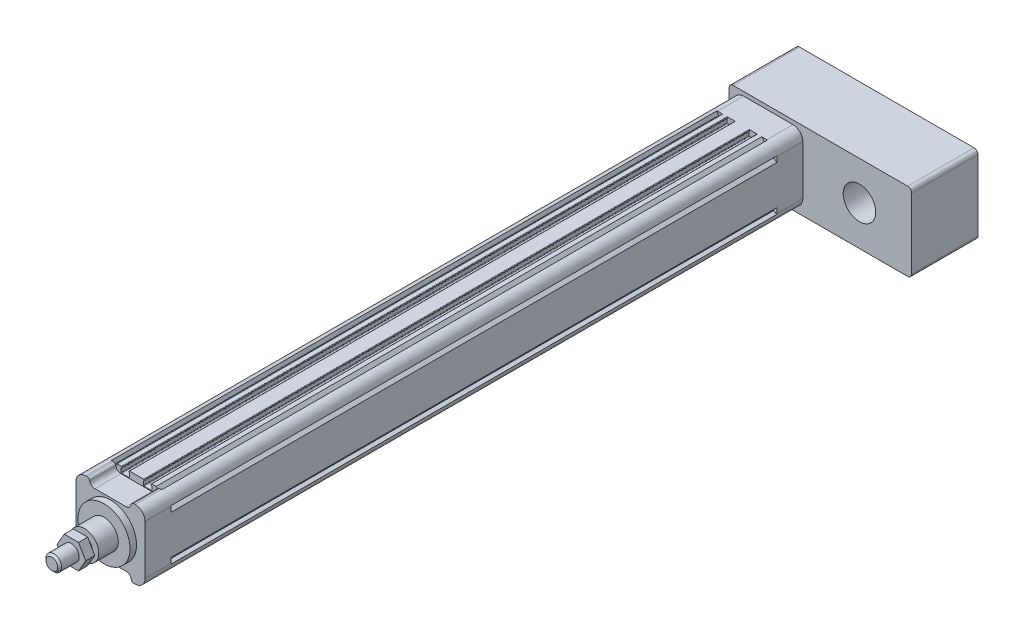
SolidWorks part; units mm, degrees
ref_plane "Front" through (0, 0, 0) normal (0, 0, 1) x (1, 0, 0)
ref_plane "Top" through (0, 0, 0) normal (0, 1, 0) x (1, 0, 0)
ref_plane "Right" through (0, 0, 0) normal (1, 0, 0) x (0, 0, -1)
sketch "草图1" plane through (0, 0, 0) normal (0, 0, 1) x (1, 0, 0)
  line L0 (19.7737, 3) -> (23.3, 3)
  line L1 (23.3, 3) -> (23.3, -3)
  line L2 (23.3, -3) -> (19.7737, -3)
  line L3 (-19.7737, -3) -> (-23.3, -3)
  line L4 (-23.3, -3) -> (-23.3, 3)
  line L5 (-23.3, 3) -> (-19.7737, 3)
  line L6 (-18.2, 24) -> (-19.4434, 26.4869)
  line L7 (-26.4869, 19.4434) -> (-24, 18.2)
  line L8 (-24, 18.2) -> (-24, 17.1)
  line L9 (-24, 17.1) -> (-26.5, 15)
  line L10 (-26.5, 15) -> (-26.5, -15)
  line L11 (-26.5, -15) -> (-24, -17.1)
  line L12 (-24, -17.1) -> (-24, -18.2)
  line L13 (-24, -18.2) -> (-26.4869, -19.4434)
  line L14 (-19.4434, -26.4869) -> (-18.2, -24)
  line L15 (-18.2, -24) -> (-17.1, -24)
  line L16 (-17.1, -24) -> (-15, -26.5)
  line L17 (-15, -26.5) -> (-11.65, -26.5)
  line L18 (-11.25, -26.1) -> (-11.25, -25.6)
  line L19 (-11.65, -25.2) -> (-11.75, -25.2)
  line L20 (-11.75, -25.2) -> (-11.75, -22.4)
  line L21 (-11.35, -22) -> (-5.65, -22)
  line L22 (-5.25, -22.4) -> (-5.25, -25.2)
  line L23 (-5.25, -25.2) -> (-5.35, -25.2)
  line L24 (-5.75, -25.6) -> (-5.75, -26.1)
  line L25 (-5.35, -26.5) -> (5.35, -26.5)
  line L26 (5.75, -26.1) -> (5.75, -25.6)
  line L27 (5.35, -25.2) -> (5.25, -25.2)
  line L28 (5.25, -25.2) -> (5.25, -22.4)
  line L29 (5.65, -22) -> (11.35, -22)
  line L30 (11.75, -22.4) -> (11.75, -25.2)
  line L31 (11.75, -25.2) -> (11.65, -25.2)
  line L32 (11.25, -25.6) -> (11.25, -26.1)
  line L33 (11.65, -26.5) -> (15, -26.5)
  line L34 (15, -26.5) -> (17.1, -24)
  line L35 (17.1, -24) -> (18.2, -24)
  line L36 (18.2, -24) -> (19.4434, -26.4869)
  line L37 (26.4869, -19.4434) -> (24, -18.2)
  line L38 (24, -18.2) -> (24, -17.1)
  line L39 (24, -17.1) -> (26.5, -15)
  line L40 (26.5, -15) -> (26.5, 15)
  line L41 (26.5, 15) -> (24, 17.1)
  line L42 (24, 17.1) -> (24, 18.2)
  line L43 (24, 18.2) -> (26.4869, 19.4434)
  line L44 (19.4434, 26.4869) -> (18.2, 24)
  line L45 (18.2, 24) -> (17.1, 24)
  line L46 (17.1, 24) -> (15, 26.5)
  line L47 (15, 26.5) -> (11.65, 26.5)
  line L48 (11.25, 26.1) -> (11.25, 25.6)
  line L49 (11.65, 25.2) -> (11.75, 25.2)
  line L50 (11.75, 25.2) -> (11.75, 22.4)
  line L51 (11.35, 22) -> (5.65, 22)
  line L52 (5.25, 22.4) -> (5.25, 25.2)
  line L53 (5.25, 25.2) -> (5.35, 25.2)
  line L54 (5.75, 25.6) -> (5.75, 26.1)
  line L55 (5.35, 26.5) -> (-5.35, 26.5)
  line L56 (-5.75, 26.1) -> (-5.75, 25.6)
  line L57 (-5.35, 25.2) -> (-5.25, 25.2)
  line L58 (-5.25, 25.2) -> (-5.25, 22.4)
  line L59 (-5.65, 22) -> (-11.35, 22)
  line L60 (-11.75, 22.4) -> (-11.75, 25.2)
  line L61 (-11.75, 25.2) -> (-11.65, 25.2)
  line L62 (-11.25, 25.6) -> (-11.25, 26.1)
  line L63 (-11.65, 26.5) -> (-15, 26.5)
  line L64 (-15, 26.5) -> (-17.1, 24)
  line L65 (-17.1, 24) -> (-18.2, 24)
  arc A0 (19.7737, 3) -> (-19.7737, 3) centre (0, 0) ccw
  arc A1 (-19.7737, -3) -> (19.7737, -3) centre (0, 0) ccw
  circle A2 centre (19, 19) radius 2.1
  circle A3 centre (19, -19) radius 2.1
  circle A4 centre (-19, -19) radius 2.1
  circle A5 centre (-19, 19) radius 2.1
  arc A6 (-19.4434, 26.4869) -> (-26.4869, 19.4434) centre (-19, 19) ccw
  arc A7 (-26.4869, -19.4434) -> (-19.4434, -26.4869) centre (-19, -19) ccw
  arc A8 (-11.65, -26.5) -> (-11.25, -26.1) centre (-11.65, -26.1) ccw
  arc A9 (-11.25, -25.6) -> (-11.65, -25.2) centre (-11.65, -25.6) ccw
  arc A10 (-11.35, -22) -> (-11.75, -22.4) centre (-11.35, -22.4) ccw
  arc A11 (-5.25, -22.4) -> (-5.65, -22) centre (-5.65, -22.4) ccw
  arc A12 (-5.35, -25.2) -> (-5.75, -25.6) centre (-5.35, -25.6) ccw
  arc A13 (-5.75, -26.1) -> (-5.35, -26.5) centre (-5.35, -26.1) ccw
  arc A14 (5.35, -26.5) -> (5.75, -26.1) centre (5.35, -26.1) ccw
  arc A15 (5.75, -25.6) -> (5.35, -25.2) centre (5.35, -25.6) ccw
  arc A16 (5.65, -22) -> (5.25, -22.4) centre (5.65, -22.4) ccw
  arc A17 (11.75, -22.4) -> (11.35, -22) centre (11.35, -22.4) ccw
  arc A18 (11.65, -25.2) -> (11.25, -25.6) centre (11.65, -25.6) ccw
  arc A19 (11.25, -26.1) -> (11.65, -26.5) centre (11.65, -26.1) ccw
  arc A20 (19.4434, -26.4869) -> (26.4869, -19.4434) centre (19, -19) ccw
  arc A21 (26.4869, 19.4434) -> (19.4434, 26.4869) centre (19, 19) ccw
  arc A22 (11.65, 26.5) -> (11.25, 26.1) centre (11.65, 26.1) ccw
  arc A23 (11.25, 25.6) -> (11.65, 25.2) centre (11.65, 25.6) ccw
  arc A24 (11.35, 22) -> (11.75, 22.4) centre (11.35, 22.4) ccw
  arc A25 (5.25, 22.4) -> (5.65, 22) centre (5.65, 22.4) ccw
  arc A26 (5.35, 25.2) -> (5.75, 25.6) centre (5.35, 25.6) ccw
  arc A27 (5.75, 26.1) -> (5.35, 26.5) centre (5.35, 26.1) ccw
  arc A28 (-5.35, 26.5) -> (-5.75, 26.1) centre (-5.35, 26.1) ccw
  arc A29 (-5.75, 25.6) -> (-5.35, 25.2) centre (-5.35, 25.6) ccw
  arc A30 (-5.65, 22) -> (-5.25, 22.4) centre (-5.65, 22.4) ccw
  arc A31 (-11.75, 22.4) -> (-11.35, 22) centre (-11.35, 22.4) ccw
  arc A32 (-11.65, 25.2) -> (-11.25, 25.6) centre (-11.65, 25.6) ccw
  arc A33 (-11.25, 26.1) -> (-11.65, 26.5) centre (-11.65, 26.1) ccw
extrude "凸台-拉伸1" add sketch "草图1" along normal blind 465
sketch "草图6" plane through (0, 0, 465) normal (0, 0, 1) x (1, 0, 0)
  line L0 (0, 0) -> (19, 0) construction
  line L2 (-26.5, -19) -> (-26.5, 19)
  line L3 (-19, 26.5) -> (-17.9161, 26.5)
  line L4 (26.5, -19) -> (26.5, 19)
  line L5 (-26.5, -26.5) -> (26.5, 26.5) construction
  line L6 (-26.5, 26.5) -> (26.5, -26.5) construction
  line L7 (-12, 21.5) -> (12, 21.5)
  line L9 (19, 26.5) -> (17.9161, 26.5)
  line L10 (19, -26.5) -> (17.9161, -26.5)
  line L11 (-12, -21.5) -> (12, -21.5)
  line L12 (-19, -26.5) -> (-17.9161, -26.5)
  arc A0 (12, 21.5) -> (15.9441, 24.8333) centre (12, 25.5) ccw
  arc A1 (-15.9441, 24.8333) -> (-12, 21.5) centre (-12, 25.5) ccw
  arc A2 (-15.9441, 24.8333) -> (-17.9161, 26.5) centre (-17.9161, 24.5) ccw
  arc A3 (15.9441, 24.8333) -> (17.9161, 26.5) centre (17.9161, 24.5) cw
  arc A4 (-26.5, -19) -> (-19, -26.5) centre (-19, -19) ccw
  arc A5 (19, -26.5) -> (26.5, -19) centre (19, -19) ccw
  arc A6 (26.5, 19) -> (19, 26.5) centre (19, 19) ccw
  arc A7 (-26.5, 19) -> (-19, 26.5) centre (-19, 19) cw
  arc A8 (15.9441, -24.8333) -> (17.9161, -26.5) centre (17.9161, -24.5) ccw
  arc A9 (12, -21.5) -> (15.9441, -24.8333) centre (12, -25.5) cw
  arc A10 (-15.9441, -24.8333) -> (-12, -21.5) centre (-12, -25.5) cw
  arc A11 (-15.9441, -24.8333) -> (-17.9161, -26.5) centre (-17.9161, -24.5) cw
  point P0 (0, 0)
  point P9 (0, 21.5)
  point P13 (20, 20.8461)
  point P16 (-12, 20.8461)
  dimension "D5" = 4
  dimension "D6" = 2
  dimension "D7" = 2
  dimension "D9" = 7.5
  dimension "D1" = 53
  dimension "D2" = 53
  dimension "D3" = 26.5
  dimension "D4" = 24
  dimension "D8" = 5
extrude "凸台-拉伸2" add sketch "草图6" along normal blind 20
sketch "草图7" plane through (0, 0, 485) normal (0, 0, 1) x (1, 0, 0)
  circle A0 centre (0, 0) radius 20
  dimension "D1" = 40
extrude "凸台-拉伸3" add sketch "草图7" along normal blind 5
sketch "草图9" plane through (0, 0, 490) normal (0, 0, 1) x (1, 0, 0)
  circle A0 centre (0, 0) radius 11
  dimension "D1" = 22
extrude "凸台-拉伸4" add sketch "草图9" along normal blind 15
sketch "草图10" plane through (0, 0, 505) normal (0, 0, 1) x (1, 0, 0)
  circle A0 centre (0, 0) radius 6
  dimension "D1" = 12
extrude "凸台-拉伸5" add sketch "草图10" along normal blind 25
sketch "草图11" plane through (0, 0, 0) normal (0, 0, -1) x (-1, 0, 0)
  line L1 (-19, -26.5) -> (19, -26.5)
  line L2 (-26.5, -19) -> (-26.5, 19)
  line L3 (-19, 26.5) -> (19, 26.5)
  line L4 (26.5, -19) -> (26.5, 19)
  line L5 (-26.5, -26.5) -> (26.5, 26.5) construction
  line L6 (-26.5, 26.5) -> (26.5, -26.5) construction
  arc A0 (-26.5, -19) -> (-19, -26.5) centre (-19, -19) ccw
  arc A1 (19, -26.5) -> (26.5, -19) centre (19, -19) ccw
  arc A2 (26.5, 19) -> (19, 26.5) centre (19, 19) ccw
  arc A3 (-26.5, 19) -> (-19, 26.5) centre (-19, 19) cw
  point P0 (0, 0)
  dimension "D3" = 7.5
  dimension "D1" = 53
  dimension "D2" = 53
extrude "凸台-拉伸6" add sketch "草图11" along normal blind 20
sketch "草图12" plane through (0, 0, -20) normal (0, 0, -1) x (-1, 0, 0)
  line L1 (-107, -30.4042) -> (27, -30.4042)
  line L2 (-110, -27.4042) -> (-110, 26.5958)
  line L3 (-107, 29.5958) -> (27, 29.5958)
  line L4 (30, -27.4042) -> (30, 26.5958)
  line L5 (-110, -30.4042) -> (30, 29.5958) construction
  line L6 (-110, 29.5958) -> (30, -30.4042) construction
  arc A0 (27, 29.5958) -> (30, 26.5958) centre (27, 26.5958) cw
  arc A1 (30, -27.4042) -> (27, -30.4042) centre (27, -27.4042) cw
  arc A2 (-110, -27.4042) -> (-107, -30.4042) centre (-107, -27.4042) ccw
  arc A3 (-110, 26.5958) -> (-107, 29.5958) centre (-107, 26.5958) cw
  point P0 (-40, -0.4042)
  dimension "D4" = 3
  dimension "D1" = 60
  dimension "D2" = 140
  dimension "D3" = 30
extrude "凸台-拉伸7" add sketch "草图12" along normal blind 51
sketch "草图13" plane through (0, 0, -20) normal (0, 0, 1) x (1, 0, 0)
  circle A0 centre (70, 0) radius 12.5
  dimension "D2" = 25
  dimension "D1" = 70
extrude "切除-拉伸2" cut sketch "草图13" against normal blind 30
hole_wizard "M6 螺纹孔1" positions "草图14" profile "草图15" tap size "M6" standard "GB"
sketch "草图14" plane through (0, 0, -71) normal (0, 0, -1) x (-1, 0, 0)
  line L0 (30, -27.4042) -> (30, 26.5958) construction
  point P0 (19, -19)
  dimension "D1" = 11
  dimension "D2" = 19
sketch "草图15" plane through (-19, -19, -71) normal (1, 0, 0) x (0, 1, 0)
  line L0 (0, 0) -> (0, 16.5022)
  line L1 (0, 16.5022) -> (2.5, 15)
  line L2 (2.5, 15) -> (2.5, 0)
  line L5 (2.5, 0) -> (0, 0)
  line L10 (0, 16.5022) -> (-2.5, 15) construction
  line L11 (0, -6.35) -> (0, 107.95) construction
  dimension "螺纹孔钻头直径" = 5
  dimension "螺纹孔钻头深度" = 15
  dimension "导头角度" = 118
cosmetic thread "孔螺蚊线4" parameters "D1"=12, "D2"=6
pattern_linear "阵列(线性)1" count 2 spacing 38 along (0, 1, 0) count 2 spacing 38 along (1, 0, 0) of "M6 螺纹孔1"
hole_wizard "M6 螺纹孔2" positions "草图16" profile "草图17" tap size "M6" standard "GB"
sketch "草图16" plane through (0, 0, -71) normal (0, 0, -1) x (-1, 0, 0)
  circle A1 centre (-19, 19) radius 2.5 construction
  circle A2 centre (-19, -19) radius 2.5 construction
  point P0 (-84, -19)
  point P2 (-84, 19)
  dimension "D3" = 65
  dimension "D1" = 19
  dimension "D2" = 19
  dimension "D4" = 65
sketch "草图17" plane through (84, -19, -71) normal (1, 0, 0) x (0, 1, 0)
  line L0 (0, 0) -> (0, 16.5022)
  line L1 (0, 16.5022) -> (2.5, 15)
  line L2 (2.5, 15) -> (2.5, 0)
  line L5 (2.5, 0) -> (0, 0)
  line L10 (0, 16.5022) -> (-2.5, 15) construction
  line L11 (0, -6.35) -> (0, 107.95) construction
  dimension "螺纹孔钻头直径" = 5
  dimension "螺纹孔钻头深度" = 15
  dimension "导头角度" = 118
cosmetic thread "孔螺蚊线5" parameters "D1"=12, "D2"=6
cosmetic thread "孔螺蚊线6" parameters "D1"=12, "D2"=6
hole_wizard "M6 螺纹孔3" positions "草图19" profile "草图20" tap size "M6" standard "GB"
sketch "草图19" plane through (-26.5, 0, 0) normal (-1, 0, 0) x (0, 0, 1)
  line L0 (485, 19) -> (485, -19) construction
  point P0 (475, 11)
  point P2 (475, -11)
  dimension "D1" = 10
  dimension "D2" = 10
  dimension "D3" = 22
  dimension "D4" = 11
sketch "草图20" plane through (-26.5, 11, 475) normal (0, 1, 0) x (0, 0, 1)
  line L0 (0, 0) -> (0, 16.5022)
  line L1 (0, 16.5022) -> (2.5, 15)
  line L2 (2.5, 15) -> (2.5, 0)
  line L5 (2.5, 0) -> (0, 0)
  line L10 (0, 16.5022) -> (-2.5, 15) construction
  line L11 (0, -6.35) -> (0, 107.95) construction
  dimension "螺纹孔钻头直径" = 5
  dimension "螺纹孔钻头深度" = 15
  dimension "导头角度" = 118
cosmetic thread "孔螺蚊线7" parameters "D1"=12, "D2"=6
cosmetic thread "孔螺蚊线8" parameters "D1"=12, "D2"=6
hole_wizard "M6 螺纹孔4" positions "草图21" profile "草图22" tap size "M6" standard "GB"
sketch "草图21" plane through (-26.5, 0, 0) normal (-1, 0, 0) x (0, 0, 1)
  line L0 (-20, -27.4042) -> (-20, 26.5958) construction
  line L1 (-20, -19) -> (-20, 19) construction
  point P0 (-10, 11)
  point P2 (-10, -11)
  dimension "D1" = 10
  dimension "D2" = 10
  dimension "D3" = 11
  dimension "D4" = 11
sketch "草图22" plane through (-26.5, 11, -10) normal (0, 1, 0) x (0, 0, 1)
  line L0 (0, 0) -> (0, 16.5022)
  line L1 (0, 16.5022) -> (2.5, 15)
  line L2 (2.5, 15) -> (2.5, 0)
  line L5 (2.5, 0) -> (0, 0)
  line L10 (0, 16.5022) -> (-2.5, 15) construction
  line L11 (0, -6.35) -> (0, 107.95) construction
  dimension "螺纹孔钻头直径" = 5
  dimension "螺纹孔钻头深度" = 15
  dimension "导头角度" = 118
cosmetic thread "孔螺蚊线9" parameters "D1"=12, "D2"=6
cosmetic thread "孔螺蚊线10" parameters "D1"=12, "D2"=6
chamfer "倒角1" distance 1.5 angle 45 1 edges at (6, 0, 530)
sketch "草图23" plane through (0, 0, 505) normal (0, 0, 1) x (1, 0, 0)
  line L1 (10.9697, 0) -> (5.4848, 9.5)
  line L2 (5.4848, 9.5) -> (-5.4848, 9.5)
  line L3 (-5.4848, 9.5) -> (-10.9697, 0)
  line L4 (-10.9697, 0) -> (-5.4848, -9.5)
  line L5 (-5.4848, -9.5) -> (5.4848, -9.5)
  line L6 (5.4848, -9.5) -> (10.9697, 0)
  circle A0 centre (0, 0) radius 9.5 construction
  dimension "D1" = 19
extrude "凸台-拉伸8" add sketch "草图23" along normal blind 7 from offset 3
